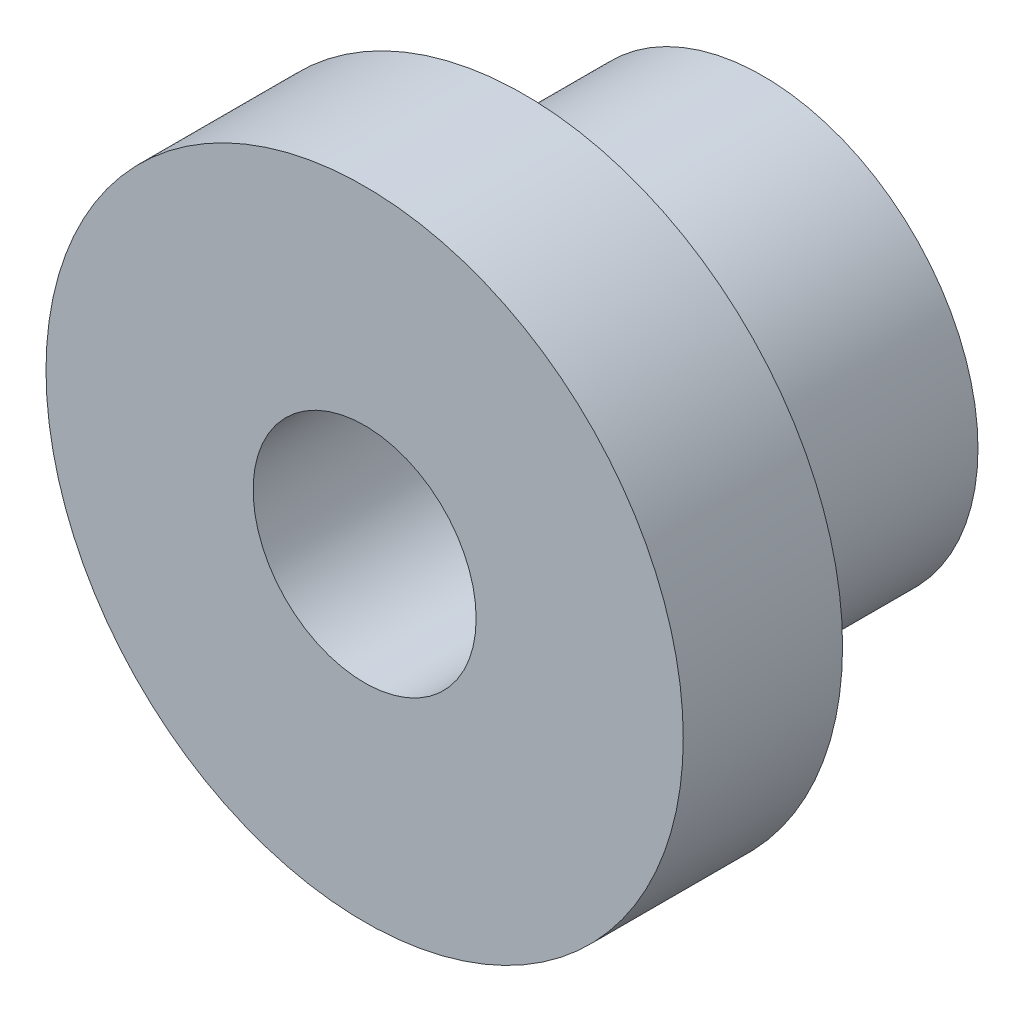
SolidWorks part; units mm, degrees
ref_plane "Front Plane" through (0, 0, 0) normal (0, 0, 1) x (1, 0, 0)
ref_plane "Top Plane" through (0, 0, 0) normal (0, 1, 0) x (1, 0, 0)
ref_plane "Right Plane" through (0, 0, 0) normal (1, 0, 0) x (0, 0, -1)
sketch "Sketch1" plane through (0, 0, 0) normal (0, 0, 1) x (1, 0, 0)
  circle A0 centre (0, 0) radius 1.65
  circle A1 centre (0, 0) radius 2.7
  dimension "D1" = 3.3
extrude "Boss-Extrude1" add sketch "Sketch1" along normal blind 3
sketch "Sketch2" plane through (0, 0, 3) normal (0, 0, 1) x (1, 0, 0)
  circle A0 centre (0, 0) radius 4
  circle A1 centre (0, 0) radius 1.4
  dimension "D1" = 8
extrude "Boss-Extrude2" add sketch "Sketch2" along normal blind 2
